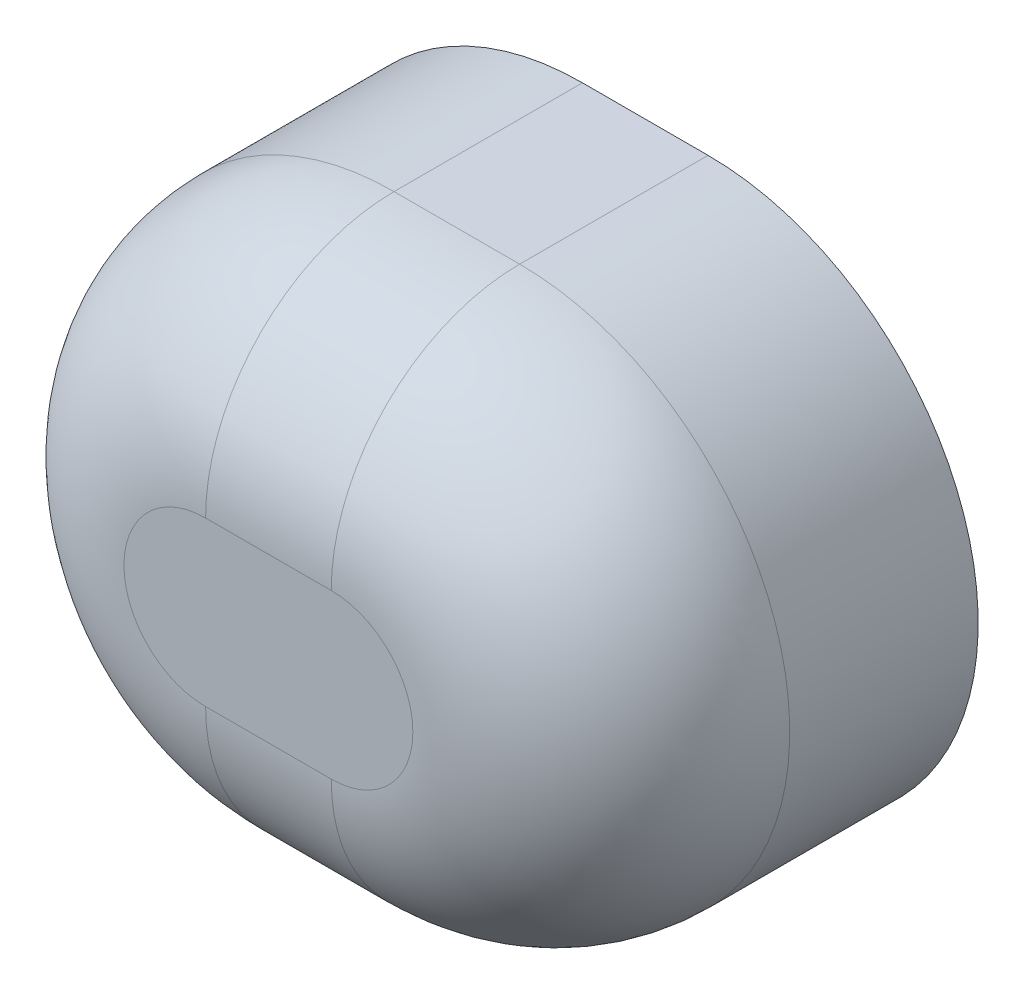
SolidWorks part; units mm, degrees
ref_plane "Płaszczyzna przednia" through (0, 0, 0) normal (0, 0, 1) x (1, 0, 0)
ref_plane "Płaszczyzna górna" through (0, 0, 0) normal (0, 1, 0) x (1, 0, 0)
ref_plane "Płaszczyzna prawa" through (0, 0, 0) normal (1, 0, 0) x (0, 0, -1)
sketch "Szkic2" plane through (0, 0, 0) normal (0, 0, 1) x (1, 0, 0)
  line L0 (-5.2455, 0) -> (-4.2455, 0) construction
  line L1 (-5.2455, 2.15) -> (-4.2455, 2.15)
  line L2 (-5.2455, -2.15) -> (-4.2455, -2.15)
  arc A0 (-5.2455, 2.15) -> (-5.2455, -2.15) centre (-5.2455, 0) ccw
  arc A1 (-4.2455, -2.15) -> (-4.2455, 2.15) centre (-4.2455, 0) ccw
  point P3 (-4.7455, 0)
extrude "Dodanie-wyciągnięcie2" add sketch "Szkic2" along normal blind 3 contours L1 A1 L2 A0
fillet "Zaokrąglenie3" radius 1.5 4 edges at (-4.7455, 2.15, 3) (-2.0955, 0, 3) (-4.7455, -2.15, 3) (-7.3955, 0, 3)
